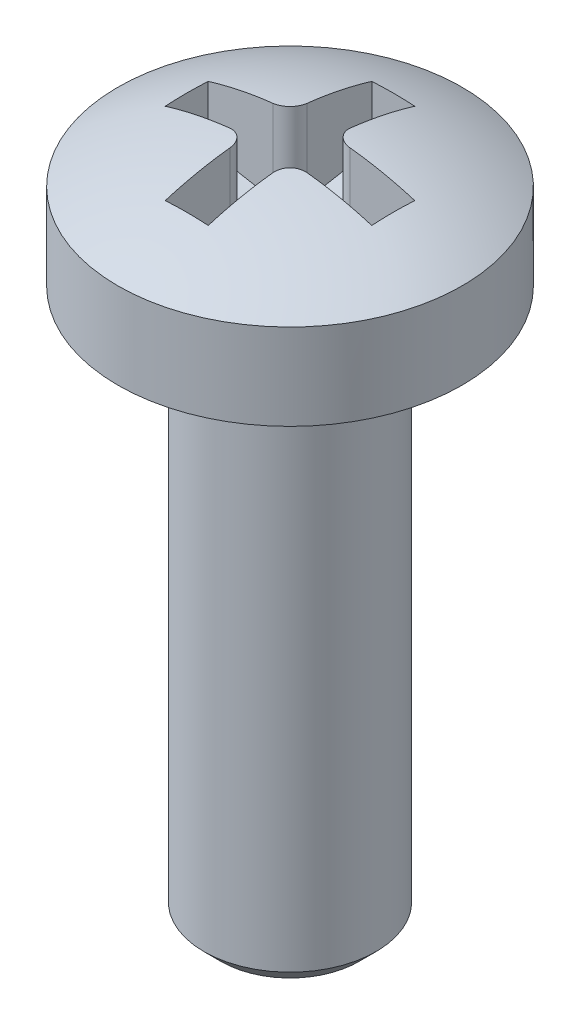
SolidWorks part; units mm, degrees
material "Cast Stainless Steel"
ref_plane "Front Plane" through (0, 0, 0) normal (0, 0, 1) x (1, 0, 0)
ref_plane "Top Plane" through (0, 0, 0) normal (0, 1, 0) x (1, 0, 0)
ref_plane "Right Plane" through (0, 0, 0) normal (1, 0, 0) x (0, 0, -1)
sketch "Sketch1" plane through (0, 0, 0) normal (0, 0, 1) x (1, 0, 0)
  line L0 (0, 0) -> (0, 3.8)
  line L1 (0, 3.8) -> (0, -22.0705) construction
  line L2 (5, 2.5) -> (5, 0)
  line L3 (5, 0) -> (2.5, 0)
  line L4 (2.5, 0) -> (2.5, -16)
  line L5 (2.5, -16) -> (0, -16)
  line L6 (0, -16) -> (0, 0)
  arc A0 (0, 3.8) -> (5, 2.5) centre (0, -6.4654) cw
  dimension "D2" = 5
  dimension "D3" = 10
  dimension "D1" = 2.5
  dimension "D4" = 3.8
  dimension "D5" = 16
revolve "Revolve1" add sketch "Sketch1" angle 360 about L1
sketch "Sketch3" plane through (0, 0, 0) normal (0, 0, 1) x (1, 0, 0)
  line L0 (5, 1.25) -> (-5, 1.25) construction
  line L1 (5, 0) -> (5, 2.5) construction
  line L2 (-5, 2.5) -> (-5, 0) construction
  line L3 (0, 0) -> (0, 1.25) construction
  arc A0 (0, 1.25) -> (5, 2.5) centre (0, 11.875) ccw
  point P3 (0, 1.25)
surface "Surface-Revolve1" sketch "Sketch3" parameters "D1"=360
sketch "Sketch4" plane through (0, 0, 0) normal (0, 1, 0) x (1, 0, 0)
  line L0 (-0.625, -0.625) -> (-0.625, -3)
  line L1 (-3, 0.625) -> (-0.625, 0.625)
  line L2 (-3, 0.625) -> (-3, -0.625)
  line L3 (-3, -0.625) -> (-0.625, -0.625)
  line L4 (3, 0.625) -> (3, -0.625)
  line L5 (-3, 0.625) -> (3, -0.625) construction
  line L6 (-3, -0.625) -> (3, 0.625) construction
  line L7 (-0.625, 3) -> (0.625, 3)
  line L8 (-0.625, 3) -> (-0.625, 0.625)
  line L9 (-0.625, -3) -> (0.625, -3)
  line L10 (0.625, 3) -> (0.625, 0.625)
  line L11 (-0.625, 3) -> (0.625, -3) construction
  line L12 (-0.625, -3) -> (0.625, 3) construction
  line L13 (0.625, 0.625) -> (3, 0.625)
  line L14 (0.625, -0.625) -> (0.625, -3)
  line L15 (0.625, -0.625) -> (3, -0.625)
  point P0 (0, 0)
  point P6 (0, 0)
  dimension "D3" = 1.25
  dimension "D4" = 1.25
  dimension "D1" = 6
  dimension "D2" = 6
extrude "Cut-Extrude1" cut sketch "Sketch4" against normal up to surface (18.2985 mm away) from offset 20
delete or keep bodies "Body-Delete/Keep 1" type delete bodies bodies 102
fillet "Fillet1" radius 0.5 4 edges at (0.625, 2.5244, -0.625) (0.625, 2.5244, 0.625) (-0.625, 2.5244, 0.625) (-0.625, 2.5244, -0.625)
chamfer "Chamfer1" distance 0.5 angle 45 1 edges at (0, -16, 2.5)
equation "\"d1\"=5"
equation "\"d2\"= 10"
equation "\"k\"= 3.8"
equation "\"v\"= 2.5"
equation "\"D1@Sketch1\"=\"v\""
equation "\"D3@Sketch1\"=\"d2\""
equation "\"D2@Sketch1\"= \"d1\""
equation "\"D4@Sketch1\"=\"k\""
equation "\"L\"= 16"
equation "\"D5@Sketch1\"=\"L\""
equation "\"D1@Sketch4\"=\"m\""
equation "\"D2@Sketch4\"=\"m\""
equation "\"D3@Sketch4\" = \"d1\" / 4"
equation "\"D4@Sketch4\" = \"d1\" / 4"
equation "\"D1@Fillet1\"=\"d1\"/10"
equation "\"D1@Chamfer1\"=\"d1\"/10"
equation "\"m\"= 6"
